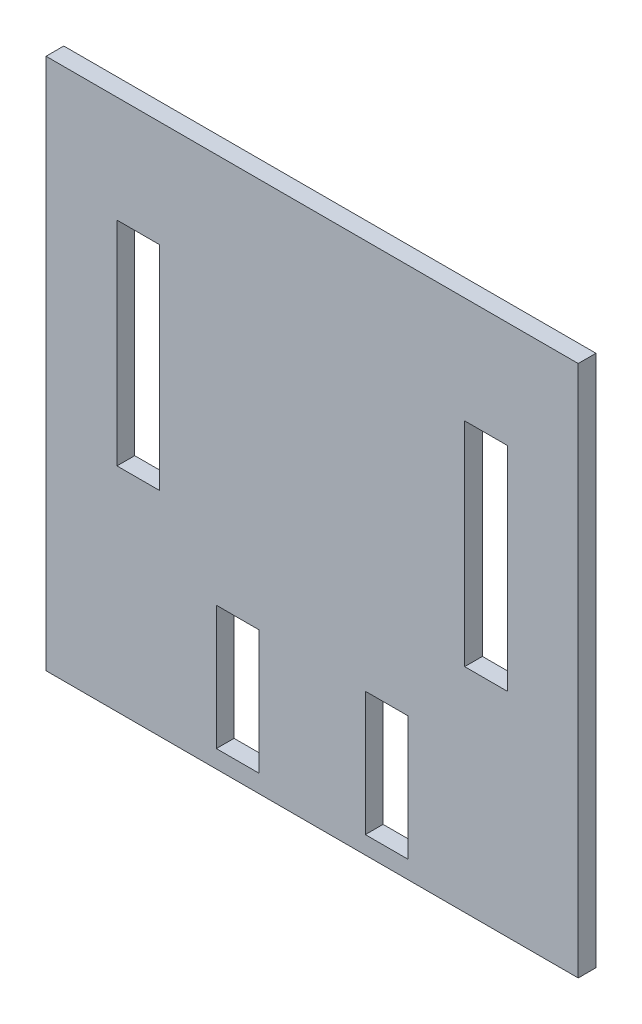
SolidWorks part; units mm, degrees
ref_plane "Plan de face" through (0, 0, 0) normal (0, 0, 1) x (1, 0, 0)
ref_plane "Plan de dessus" through (0, 0, 0) normal (0, 1, 0) x (1, 0, 0)
ref_plane "Plan de droite" through (0, 0, 0) normal (1, 0, 0) x (0, 0, -1)
sketch "Esquisse1" plane through (0, 0, 0) normal (0, 0, 1) x (1, 0, 0)
  line L1 (0, 0) -> (150, 0)
  line L2 (0, 0) -> (0, 150)
  line L3 (0, 150) -> (150, 150)
  line L4 (150, 0) -> (150, 150)
  dimension "D1" = 150
  dimension "D2" = 150
extrude "Boss.-Extru.1" add sketch "Esquisse1" along normal blind 5
sketch "Esquisse2" plane through (0, 0, 5) normal (0, 0, 1) x (1, 0, 0)
  line L0 (0, 150) -> (0, 0) construction
  line L1 (20, 120) -> (32, 120)
  line L2 (20, 120) -> (20, 60)
  line L3 (20, 60) -> (32, 60)
  line L4 (32, 120) -> (32, 60)
  line L5 (118, 120) -> (130, 120)
  line L6 (118, 120) -> (118, 60)
  line L7 (118, 60) -> (130, 60)
  line L8 (130, 120) -> (130, 60)
  line L9 (48, 40) -> (60, 40)
  line L10 (48, 40) -> (48, 5)
  line L11 (48, 5) -> (60, 5)
  line L12 (60, 40) -> (60, 5)
  line L13 (90, 40) -> (102, 40)
  line L14 (90, 40) -> (90, 5)
  line L15 (90, 5) -> (102, 5)
  line L16 (102, 40) -> (102, 5)
  line L17 (150, 0) -> (150, 150) construction
  line L18 (150, 150) -> (0, 150) construction
  line L19 (0, 0) -> (150, 0) construction
  point P20 (124, 120)
  dimension "D1" = 12
  dimension "D2" = 12
  dimension "D3" = 12
  dimension "D4" = 12
  dimension "D5" = 35
  dimension "D6" = 35
  dimension "D7" = 60
  dimension "D8" = 60
  dimension "D9" = 20
  dimension "D10" = 20
  dimension "D11" = 30
  dimension "D12" = 30
  dimension "D13" = 30
  dimension "D14" = 48
  dimension "D15" = 40
  dimension "D16" = 40
extrude "Enlèv. mat.-Extru.1" cut sketch "Esquisse2" against normal blind 5
